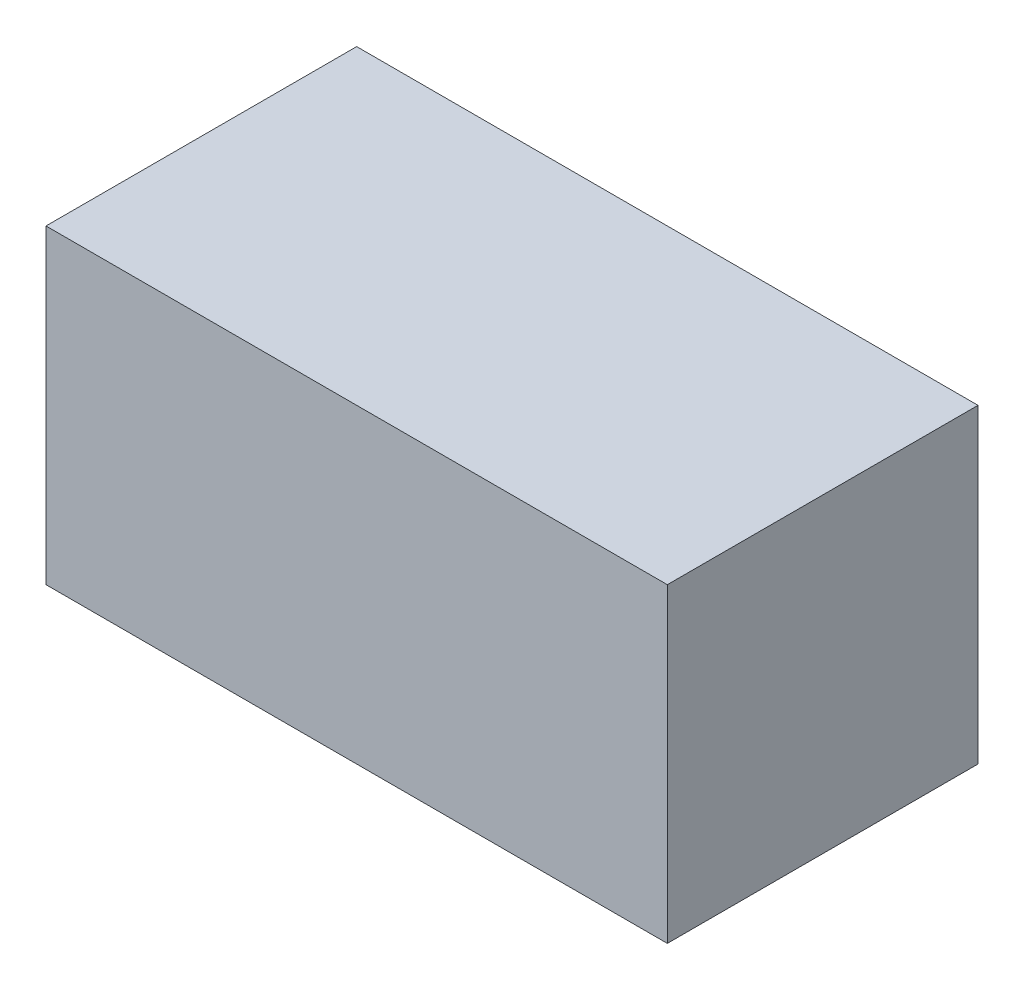
SolidWorks part; units mm, degrees
material "Plain Carbon Steel"
ref_plane "Front Plane" through (0, 0, 0) normal (0, 0, 1) x (1, 0, 0)
ref_plane "Top Plane" through (0, 0, 0) normal (0, 1, 0) x (1, 0, 0)
ref_plane "Right Plane" through (0, 0, 0) normal (1, 0, 0) x (0, 0, -1)
sketch "Sketch1" plane through (0, 0, 0) normal (0, 0, 1) x (1, 0, 0)
  line L1 (-6.35, -3.175) -> (6.35, -3.175)
  line L2 (-6.35, -3.175) -> (-6.35, 3.175)
  line L3 (-6.35, 3.175) -> (6.35, 3.175)
  line L4 (6.35, -3.175) -> (6.35, 3.175)
  line L5 (-6.35, -3.175) -> (6.35, 3.175) construction
  line L6 (-6.35, 3.175) -> (6.35, -3.175) construction
  point P0 (0, 0)
  dimension "D1" = 12.7
  dimension "D2" = 6.35
extrude "Extrude1" add sketch "Sketch1" along normal blind 6.35
